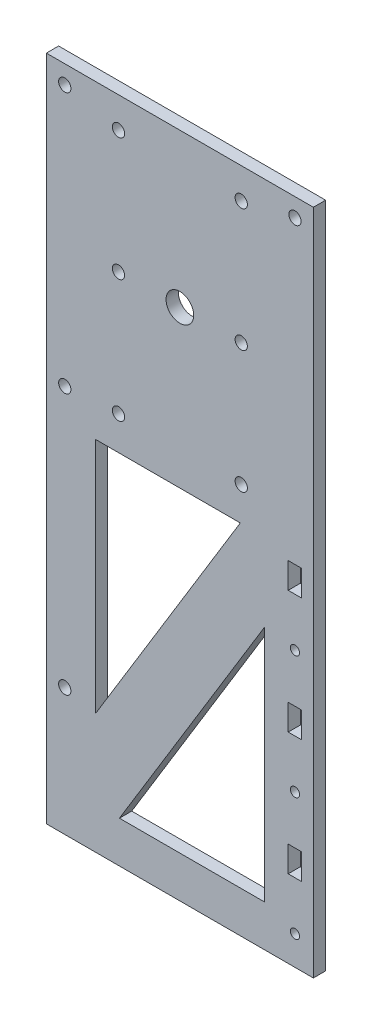
SolidWorks part; units mm, degrees
ref_plane "前视基准面" through (0, 0, 0) normal (0, 0, 1) x (1, 0, 0)
ref_plane "上视基准面" through (0, 0, 0) normal (0, 1, 0) x (1, 0, 0)
ref_plane "右视基准面" through (0, 0, 0) normal (1, 0, 0) x (0, 0, -1)
sketch "草图1" plane through (0, 0, 0) normal (0, 0, 1) x (1, 0, 0)
  line L0 (0, 20) -> (37.5, 20) construction
  line L1 (-37.5, 50) -> (37.5, 50)
  line L2 (-37.5, 50) -> (-37.5, -164) construction
  line L3 (-37.5, -164) -> (37.5, -164)
  line L4 (37.5, 50) -> (37.5, -164) construction
  line L5 (0, 20) -> (-37.5, 20) construction
  line L6 (37.5, -57) -> (43.5, -57) construction
  line L7 (43.5, -57) -> (43.5, -164)
  line L8 (43.5, -164) -> (37.5, -164)
  line L9 (-37.5, -57) -> (-43.5, -57) construction
  line L10 (-43.5, -57) -> (-43.5, -164)
  line L11 (-43.5, -164) -> (-37.5, -164)
  line L12 (-37.5, 50) -> (-37.5, -57) construction
  line L13 (37.5, -57) -> (37.5, 50) construction
  line L14 (-43.5, -57) -> (-43.5, 50)
  line L15 (-43.5, 50) -> (-37.5, 50)
  line L16 (43.5, -57) -> (43.5, 50)
  line L17 (43.5, 50) -> (37.5, 50)
  line L18 (0, 0) -> (0, -53) construction
  line L19 (-37.5, -41) -> (37.5, -41) construction
  line L20 (37.5, -41) -> (-37.5, -164) construction
  line L21 (-37.5, -41) -> (-37.5, -164) construction
  line L22 (-27.5, -51) -> (-27.5, -128.3917)
  line L23 (-27.5, -51) -> (19.69, -51)
  line L24 (19.69, -51) -> (-27.5, -128.3917)
  line L25 (37.5, -41) -> (37.5, -164) construction
  line L26 (27.5, -76.6083) -> (-19.69, -154)
  line L27 (-19.69, -154) -> (27.5, -154)
  line L28 (27.5, -76.6083) -> (27.5, -154)
  circle A0 centre (0, 0) radius 4.5
  circle A2 centre (20, 0) radius 2
  circle A3 centre (0, 20) radius 2 construction
  circle A4 centre (-20, 0) radius 2
  circle A5 centre (-20, 40) radius 2
  circle A6 centre (20, 40) radius 2
  circle A7 centre (-20, -40) radius 2
  circle A8 centre (20, -40) radius 2
  circle A9 centre (37.5, 44) radius 2
  circle A10 centre (-37.5, 44) radius 2
  circle A11 centre (-37.5, -41) radius 2
  circle A12 centre (-37.5, -126) radius 2
  dimension "D1" = 9
  dimension "D4" = 4
  dimension "D9" = 40
  dimension "D12" = 6
  dimension "D13" = 85
  dimension "D14" = 85
  dimension "D2" = 20
  dimension "D3" = 20
  dimension "D6" = 37.5
  dimension "D7" = 214
  dimension "D8" = 10
  dimension "D10" = 40
  dimension "D11" = 6
  dimension "D15" = 10
  dimension "D16" = 10
  dimension "D5" = 4
extrude "凸台-拉伸1" add sketch "草图1" along normal blind 4 contours L3 L4 L1 L2
sketch "草图2" plane through (0, 0, 4) normal (0, 0, 1) x (1, 0, 0)
  line L0 (37.5, -78) -> (37.5, -158) construction
  line L2 (43.5, -164) -> (37.5, -158) construction
  line L4 (35.3, -133.8) -> (39.7, -133.8)
  line L9 (-43.5, -164) -> (43.5, -164) construction
  line L11 (35.3, -133.8) -> (35.3, -142.2)
  line L16 (0, 0) -> (0, -38.3122) construction
  line L20 (-37.5, -64) -> (-37.5, -145.909) construction
  line L21 (35.3, -142.2) -> (39.7, -142.2)
  line L22 (39.7, -133.8) -> (39.7, -142.2)
  line L23 (35.3, -133.8) -> (39.7, -142.2) construction
  line L24 (35.3, -142.2) -> (39.7, -133.8) construction
  line L25 (39.7, -102.2) -> (39.7, -93.8)
  line L26 (35.3, -93.8) -> (39.7, -93.8)
  line L27 (35.3, -102.2) -> (35.3, -93.8)
  line L28 (35.3, -102.2) -> (39.7, -102.2)
  line L29 (37.5, -78) -> (40.1693, -78) construction
  line L30 (35.3, -62.2) -> (39.7, -62.2)
  line L31 (35.3, -53.8) -> (35.3, -62.2)
  line L32 (35.3, -53.8) -> (39.7, -53.8)
  line L33 (39.7, -53.8) -> (39.7, -62.2)
  line L35 (43.5, -164) -> (43.5, 50) construction
  circle A2 centre (37.5, -158) radius 1.5
  circle A3 centre (37.5, -78) radius 1.5
  circle A4 centre (37.5, -118) radius 1.5
  point P3 (37.5, -138)
  dimension "D2" = 6
  dimension "D1" = 6
extrude "切除-拉伸1" cut sketch "草图2" against normal blind 4
chamfer "倒角1" [suppressed] distance 2.6 angle 45
sketch "草图3" plane through (0, 0, 4) normal (0, 0, 1) x (1, 0, 0)
  line L1 (-43.5, -164) -> (43.5, -164)
  line L2 (-43.5, -164) -> (-43.5, -167.5)
  line L3 (-43.5, -167.5) -> (43.5, -167.5)
  line L4 (43.5, -164) -> (43.5, -167.5)
extrude "凸台-拉伸2" add sketch "草图3" against normal blind 4
